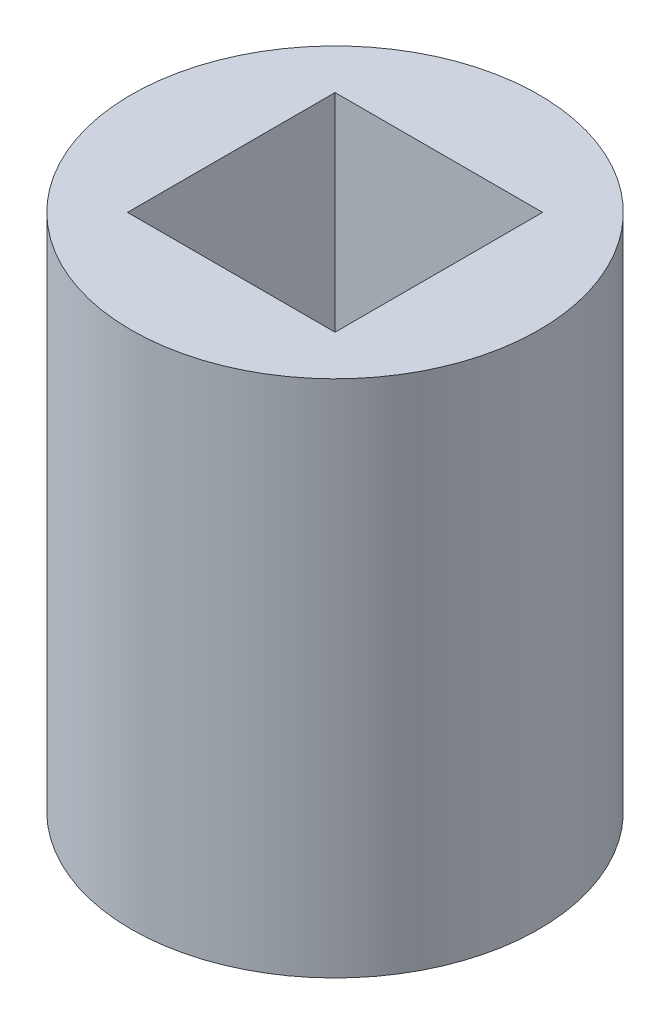
SolidWorks part; units mm, degrees
ref_plane "Front Plane" through (0, 0, 0) normal (0, 0, 1) x (1, 0, 0)
ref_plane "Top Plane" through (0, 0, 0) normal (0, 1, 0) x (1, 0, 0)
ref_plane "Right Plane" through (0, 0, 0) normal (1, 0, 0) x (0, 0, -1)
sketch "Sketch1" plane through (0, 0, 0) normal (0, 1, 0) x (1, 0, 0)
  circle A0 centre (0, 0) radius 5.5
  dimension "D1" = 11
extrude "Boss-Extrude1" add sketch "Sketch1" along normal blind 14
sketch "Sketch2" plane through (0, 14, 0) normal (0, 1, 0) x (1, 0, 0)
  line L1 (-2.8, -2.8) -> (2.8, -2.8)
  line L2 (-2.8, -2.8) -> (-2.8, 2.8)
  line L3 (-2.8, 2.8) -> (2.8, 2.8)
  line L4 (2.8, -2.8) -> (2.8, 2.8)
  line L5 (-2.8, -2.8) -> (2.8, 2.8) construction
  line L6 (-2.8, 2.8) -> (2.8, -2.8) construction
  point P0 (0, 0)
  dimension "D1" = 5.6
  dimension "5.35" = 5.6
extrude "Cut-Extrude1" cut sketch "Sketch2" against normal blind 8
sketch "Sketch3" plane through (0, 0, 0) normal (0, -1, 0) x (1, 0, 0)
  circle A0 centre (0, 0) radius 3.15
  dimension "D1" = 6.3
extrude "Cut-Extrude2" [suppressed] cut sketch "Sketch3" against normal blind 4
sketch "Sketch4" [suppressed] plane through (0, 4, 0) normal (0, -1, 0) x (1, 0, 0)
  circle A0 centre (0, 0) radius 1.75
  dimension "D1" = 3.5
extrude "Cut-Extrude3" [suppressed] cut sketch "Sketch4" against normal up to next
sketch "Sketch5" plane through (0, 14, 0) normal (0, 1, 0) x (1, 0, 0)
  circle A0 centre (0, 0) radius 2.55
  dimension "D1" = 5.1
